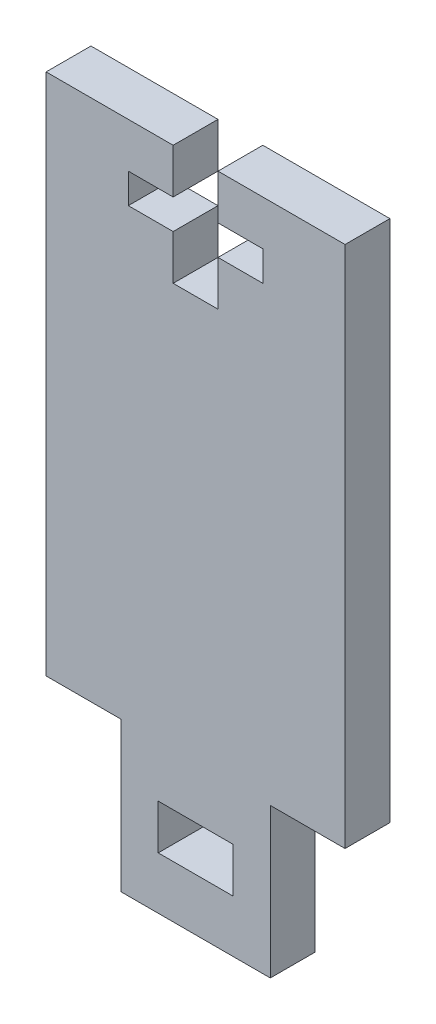
SolidWorks part; units mm, degrees
material "Maple"
ref_plane "Front Plane" through (0, 0, 0) normal (0, 0, 1) x (1, 0, 0)
ref_plane "Top Plane" through (0, 0, 0) normal (0, 1, 0) x (1, 0, 0)
ref_plane "Right Plane" through (0, 0, 0) normal (1, 0, 0) x (0, 0, -1)
sketch "Sketch1" plane through (0, 0, 0) normal (0, 0, 1) x (1, 0, 0)
  line L0 (-1.5, 17.5) -> (-1.5, 14.5)
  line L1 (-1.5, 14.5) -> (-4.5, 14.5)
  line L2 (-4.5, 14.5) -> (-4.5, 12.5)
  line L3 (-4.5, 12.5) -> (-1.5, 12.5)
  line L4 (-1.5, 12.5) -> (-1.5, 9.5)
  line L5 (-1.5, 9.5) -> (1.5, 9.5)
  line L6 (1.5, 9.5) -> (1.5, 12.5)
  line L7 (1.5, 12.5) -> (4.5, 12.5)
  line L8 (4.5, 12.5) -> (4.5, 14.5)
  line L9 (4.5, 14.5) -> (1.5, 14.5)
  line L10 (1.5, 14.5) -> (1.5, 17.5)
  line L11 (1.5, 17.5) -> (10, 17.5)
  line L12 (10, 17.5) -> (10, -17.5)
  line L13 (10, -17.5) -> (5, -17.5)
  line L14 (5, -17.5) -> (5, -27.5)
  line L15 (5, -27.5) -> (-5, -27.5)
  line L16 (-5, -27.5) -> (-5, -17.5)
  line L17 (-5, -17.5) -> (-10, -17.5)
  line L18 (-10, -17.5) -> (-10, 17.5)
  line L19 (-10, 17.5) -> (-1.5, 17.5)
  line L20 (-10, 0) -> (10, 0) construction
  line L22 (-2.5, -21) -> (2.5, -21)
  line L23 (-2.5, -21) -> (-2.5, -24)
  line L24 (-2.5, -24) -> (2.5, -24)
  line L25 (2.5, -21) -> (2.5, -24)
  line L26 (-2.5, -21) -> (2.5, -24) construction
  line L27 (-2.5, -24) -> (2.5, -21) construction
  point P22 (0, 0)
  point P23 (0, -22.5)
  point P29 (0, 0)
  dimension "D1" = 10
  dimension "D2" = 35
  dimension "D3" = 3
  dimension "D4" = 2
  dimension "D5" = 3
  dimension "D6" = 3
  dimension "D7" = 3
  dimension "D8" = 20
  dimension "D9" = 10
  dimension "D10" = 3
  dimension "D11" = 5
  dimension "D12" = 3.5
extrude "Boss-Extrude1" add sketch "Sketch1" along normal blind 3
